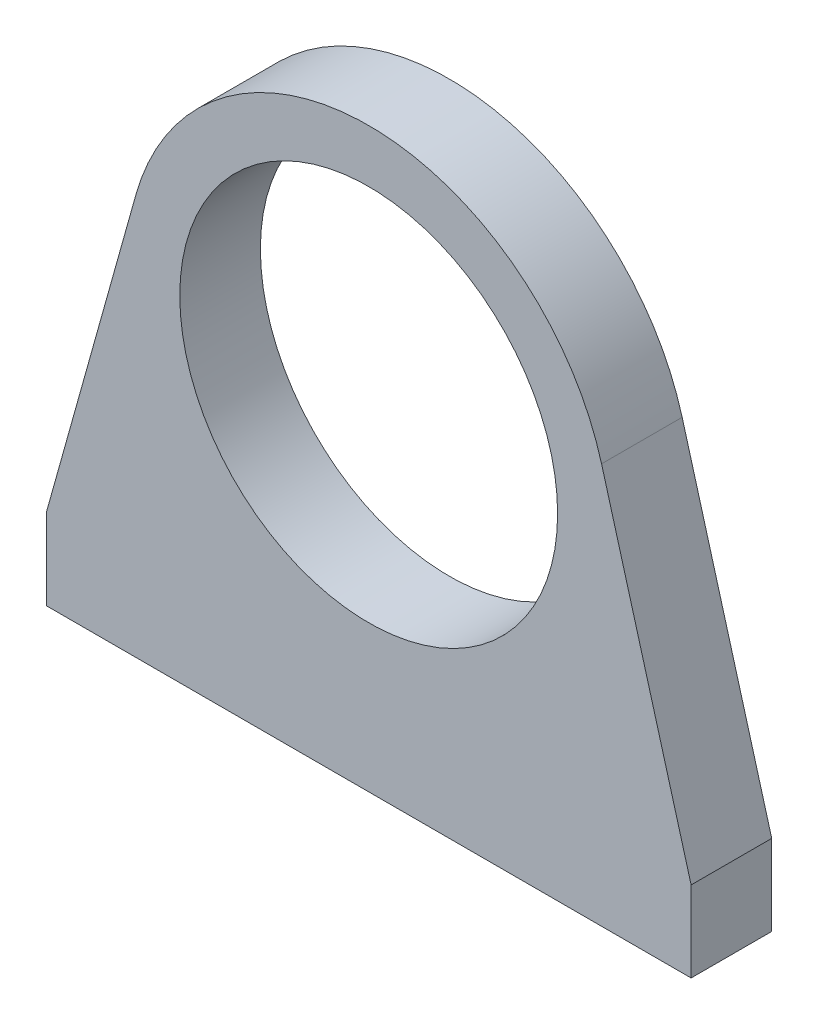
SolidWorks part; units mm, degrees
ref_plane "Front Plane" through (0, 0, 0) normal (0, 0, 1) x (1, 0, 0)
ref_plane "Top Plane" through (0, 0, 0) normal (0, 1, 0) x (1, 0, 0)
ref_plane "Right Plane" through (0, 0, 0) normal (1, 0, 0) x (0, 0, -1)
sketch "Sketch1" plane through (0, 0, 0) normal (0, 0, 1) x (1, 0, 0)
  line L0 (0, 0) -> (-25.4, 0)
  line L3 (0, 0) -> (0, 26.416) construction
  line L5 (0, 0) -> (25.4, 0)
  line L11 (-25.4, 0) -> (-25.4, 6.35)
  line L12 (-25.4, 6.35) -> (-18.3447, 31.5517)
  line L13 (18.3447, 31.5517) -> (25.4, 6.35)
  line L14 (25.4, 6.35) -> (25.4, 0)
  arc A0 (18.3447, 31.5517) -> (-18.3447, 31.5517) centre (0, 26.416) ccw
  circle A2 centre (0, 26.416) radius 26.416 construction
  point P1 (-27.7293, 5.413)
  point P10 (-25.4, 11.5371)
  dimension "D1" = 38.1
  dimension "D5" = 52.832
  dimension "D2" = 25.4
  dimension "D3" = 6.35
extrude "Boss-Extrude1" add sketch "Sketch1" along normal blind 6.35 contours A0 L12 L11 L0 L5 L14 L13
hole_wizard "1-1/4-12 Tapped Hole1" positions "3DSketch1" profile "Sketch3" tap size "1-1/4-12" standard "ANSI Inch"
sketch3d "3DSketch1"
  line L0 (0, 26.416, 6.35) -> (0, 26.416, 0) construction
  point P0 (0, 26.416, 6.35)
sketch "Sketch3" plane through (0, 26.416, 6.35) normal (1, 0, 0) x (0, -1, 0)
  line L0 (0, 0) -> (0, 83.0218)
  line L1 (0, 83.0218) -> (14.8831, 74.0791)
  line L2 (14.8831, 74.0791) -> (14.8831, 0)
  line L5 (14.8831, 0) -> (0, 0)
  line L10 (0, 83.0218) -> (-14.8831, 74.0791) construction
  line L11 (0, -6.35) -> (0, 107.95) construction
  dimension "Tap Drill Dia." = 29.7663
  dimension "Tap Drill Depth" = 74.0791
  dimension "Drill Angle" = 118
cosmetic thread "Hole Thread1" parameters "D1"=63.5, "D2"=31.75
